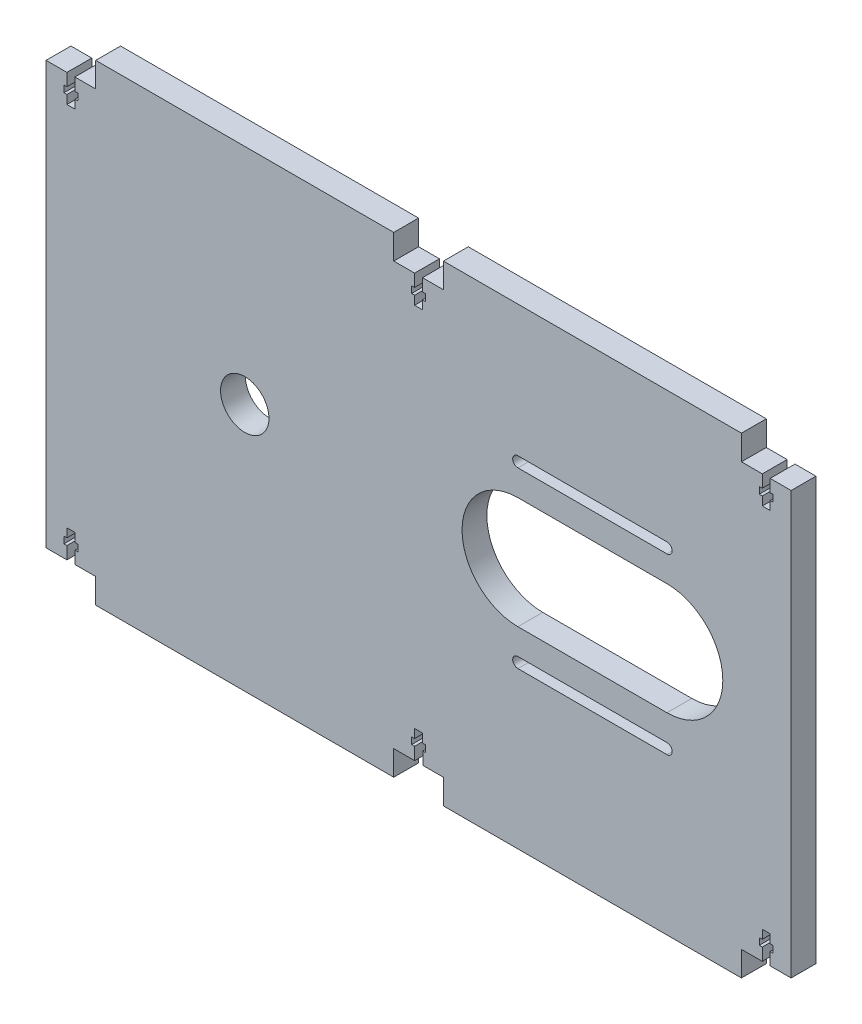
SolidWorks part; units mm, degrees
ref_plane "Ön Düzlem" through (0, 0, 0) normal (0, 0, 1) x (1, 0, 0)
ref_plane "Üst Düzlem" through (0, 0, 0) normal (0, 1, 0) x (1, 0, 0)
ref_plane "Sağ Düzlem" through (0, 0, 0) normal (1, 0, 0) x (0, 0, -1)
sketch "Çizim1" plane through (0, 0, 0) normal (0, 0, 1) x (1, 0, 0)
  line L0 (100, 10) -> (40, 10) construction
  line L1 (-150, -90) -> (150, -90)
  line L2 (-150, -90) -> (-150, 90)
  line L3 (-150, 90) -> (150, 90)
  line L4 (150, -90) -> (150, 90)
  line L5 (-150, -90) -> (150, 90) construction
  line L6 (-150, 90) -> (150, -90) construction
  line L7 (100, -12.5) -> (40, -12.5)
  line L8 (100, 32.5) -> (40, 32.5)
  line L9 (100, 45) -> (40, 45) construction
  line L10 (100, 42.9) -> (40, 42.9)
  line L11 (100, 47.1) -> (40, 47.1)
  line L12 (100, -25) -> (40, -25) construction
  line L13 (100, -27.1) -> (40, -27.1)
  line L14 (100, -22.9) -> (40, -22.9)
  arc A0 (100, -12.5) -> (100, 32.5) centre (100, 10) ccw
  circle A1 centre (-70, 10) radius 9.75
  arc A2 (40, 32.5) -> (40, -12.5) centre (40, 10) ccw
  arc A3 (100, 42.9) -> (100, 47.1) centre (100, 45) ccw
  arc A4 (40, 47.1) -> (40, 42.9) centre (40, 45) ccw
  arc A5 (100, -27.1) -> (100, -22.9) centre (100, -25) ccw
  arc A6 (40, -22.9) -> (40, -27.1) centre (40, -25) ccw
  point P0 (0, 0)
  point P8 (70, 10)
  point P17 (70, 45)
  point P22 (70, -25)
  dimension "D3" = 100
  dimension "D5" = 80
  dimension "D4" = 60
  dimension "D1" = 80
  dimension "D2" = 180
  dimension "D6" = 35
  dimension "D7" = 35
extrude "Yükseklik-Ekstrüzyon1" add sketch "Çizim1" along normal blind 10
sketch "Çizim2" plane through (0, 90, 0) normal (0, 1, 0) x (1, 0, 0)
  line L0 (130, -10) -> (130, 0)
  line L1 (130, -10) -> (10, -10)
  line L2 (130, 0) -> (10, 0)
  line L3 (10, -10) -> (10, 0)
  line L4 (150, -10) -> (-150, -10) construction
  line L5 (150, 0) -> (-150, 0) construction
  line L6 (150, -10) -> (150, 0) construction
  line L7 (-10, 0) -> (-10, -10)
  line L8 (-10, 0) -> (-130, 0)
  line L9 (-10, -10) -> (-130, -10)
  line L10 (-130, 0) -> (-130, -10)
  line L11 (-150, -10) -> (-150, 0) construction
  point P10 (0, 0)
  point P17 (0, 0)
  dimension "D1" = 20
  dimension "D2" = 10
  dimension "D3" = 20
  dimension "D4" = 10
extrude "Yükseklik-Ekstrüzyon2" add sketch "Çizim2" along normal blind 10
sketch "Çizim3" plane through (0, -90, 0) normal (0, -1, 0) x (-1, 0, 0)
  line L0 (150, -10) -> (150, 0)
  line L1 (150, -10) -> (130, -10)
  line L2 (150, 0) -> (130, 0)
  line L3 (130, -10) -> (130, 0)
  line L4 (-150, -10) -> (-150, 0)
  line L5 (-150, -10) -> (-130, -10)
  line L6 (-150, 0) -> (-130, 0)
  line L7 (-130, -10) -> (-130, 0)
  line L8 (10, 0) -> (10, -10)
  line L9 (10, 0) -> (-10, 0)
  line L10 (10, -10) -> (-10, -10)
  line L11 (-10, 0) -> (-10, -10)
  line L12 (150, 0) -> (-150, 0) construction
  line L13 (150, -10) -> (-150, -10) construction
  dimension "D1" = 120
  dimension "D2" = 20
  dimension "D3" = 20
  dimension "D4" = 20
extrude "Kes-Ekstrüzyon1" cut sketch "Çizim3" against normal blind 10
sketch "Çizim4" plane through (0, 0, 10) normal (0, 0, 1) x (1, 0, 0)
  line L0 (-142.8, 85) -> (-137.2, 85)
  line L1 (-142.8, 85) -> (-142.8, 82.3)
  line L2 (-137.2, 85) -> (-137.2, 82.3)
  line L3 (-142.8, 82.3) -> (-137.2, 82.3)
  line L4 (-130, 90) -> (-150, 90) construction
  line L5 (-10, 100) -> (-10, 90) construction
  line L6 (-2.8, 85) -> (2.8, 85)
  line L7 (-2.8, 85) -> (-2.8, 82.3)
  line L8 (-2.8, 82.3) -> (2.8, 82.3)
  line L9 (137.2, 85) -> (142.8, 85)
  line L10 (137.2, 85) -> (137.2, 82.3)
  line L11 (137.2, 82.3) -> (142.8, 82.3)
  line L12 (142.8, 85) -> (142.8, 82.3)
  line L13 (-130, -80) -> (-150, -80) construction
  line L14 (-142.8, -75) -> (-137.2, -75)
  line L15 (-142.8, -75) -> (-142.8, -72.3)
  line L16 (-142.8, -72.3) -> (-137.2, -72.3)
  line L17 (10, -80) -> (10, -90) construction
  line L18 (-2.8, -72.3) -> (2.8, -72.3)
  line L19 (-2.8, -72.3) -> (-2.8, -75)
  line L20 (-2.8, -75) -> (2.8, -75)
  line L21 (2.8, -72.3) -> (2.8, -75)
  line L22 (137.2, -72.3) -> (142.8, -72.3)
  line L23 (137.2, -72.3) -> (137.2, -75)
  line L24 (137.2, -75) -> (142.8, -75)
  line L25 (-150, 90) -> (-150, -80) construction
  line L27 (2.8, 85) -> (2.8, 82.3)
  line L28 (150, -80) -> (150, 90) construction
  line L29 (-137.2, -75) -> (-137.2, -72.3)
  line L30 (142.8, -72.3) -> (142.8, -75)
  dimension "D1" = 5
  dimension "D2" = 7.2
  dimension "D3" = 5.6
  dimension "D4" = 7.2
  dimension "D5" = 5.6
  dimension "D6" = 7.2
  dimension "D7" = 2.7
  dimension "D8" = 2.7
  dimension "D9" = 5
  dimension "D10" = 2.7
  dimension "D11" = 5.6
  dimension "D12" = 2.7
  dimension "D13" = 5.6
  dimension "D14" = 7.2
  dimension "D15" = 7.2
  dimension "D16" = 5.6
  dimension "D17" = 7.2
  dimension "D18" = 5.6
extrude "Kes-Ekstrüzyon2" cut sketch "Çizim4" against normal blind 10
sketch "Çizim5" plane through (0, 0, 10) normal (0, 0, 1) x (1, 0, 0)
  line L0 (-141.6, 82.3) -> (-138.4, 82.3)
  line L1 (-141.6, 82.3) -> (-141.6, 78.8)
  line L2 (-138.4, 82.3) -> (-138.4, 78.8)
  line L3 (-141.6, 78.8) -> (-138.4, 78.8)
  line L4 (-142.8, 82.3) -> (-137.2, 82.3) construction
  line L5 (-1.6, 82.3) -> (1.6, 82.3)
  line L6 (-1.6, 82.3) -> (-1.6, 78.8)
  line L7 (1.6, 82.3) -> (1.6, 78.8)
  line L8 (-1.6, 78.8) -> (1.6, 78.8)
  line L9 (-2.8, 82.3) -> (2.8, 82.3) construction
  line L10 (138.4, 82.3) -> (141.6, 82.3)
  line L11 (138.4, 82.3) -> (138.4, 78.8)
  line L12 (141.6, 82.3) -> (141.6, 78.8)
  line L13 (138.4, 78.8) -> (141.6, 78.8)
  line L14 (150, -80) -> (150, 90) construction
  line L15 (137.2, 82.3) -> (142.8, 82.3) construction
  line L16 (-141.6, -72.3) -> (-138.4, -72.3)
  line L17 (-141.6, -72.3) -> (-141.6, -68.8)
  line L18 (-138.4, -72.3) -> (-138.4, -68.8)
  line L19 (-141.6, -68.8) -> (-138.4, -68.8)
  line L20 (-137.2, -72.3) -> (-142.8, -72.3) construction
  line L21 (-1.6, -72.3) -> (1.6, -72.3)
  line L22 (-1.6, -72.3) -> (-1.6, -68.8)
  line L23 (1.6, -72.3) -> (1.6, -68.8)
  line L24 (-1.6, -68.8) -> (1.6, -68.8)
  line L25 (-1.6, 85) -> (-1.6, 90)
  line L26 (2.8, -72.3) -> (-2.8, -72.3) construction
  line L27 (138.4, -72.3) -> (141.6, -72.3)
  line L28 (138.4, -72.3) -> (138.4, -68.8)
  line L29 (141.6, -72.3) -> (141.6, -68.8)
  line L30 (138.4, -68.8) -> (141.6, -68.8)
  line L31 (-141.6, 85) -> (-138.4, 85)
  line L32 (142.8, -72.3) -> (137.2, -72.3) construction
  line L33 (-141.6, 85) -> (-141.6, 90.0914)
  line L34 (-138.4, 85) -> (-138.4, 90.0914)
  line L35 (-141.6, 90.0914) -> (-138.4, 90.0914)
  line L36 (-137.2, 85) -> (-142.8, 85) construction
  line L37 (-1.6, 85) -> (1.5689, 85)
  line L38 (-1.6, 90) -> (1.5689, 90)
  line L39 (1.5689, 85) -> (1.5689, 90)
  line L42 (2.8, 85) -> (-2.8, 85) construction
  line L43 (10, 90) -> (-10, 90) construction
  line L44 (138.4, 85) -> (138.4, 90)
  line L45 (138.4, 85) -> (141.5574, 85)
  line L46 (138.4, 90) -> (141.5574, 90)
  line L47 (141.5574, 85) -> (141.5574, 90)
  line L50 (142.8, 85) -> (137.2, 85) construction
  line L51 (150, 90) -> (130, 90) construction
  line L52 (138.4, -75) -> (138.4, -80)
  line L53 (138.4, -75) -> (141.5648, -75)
  line L54 (138.4, -80) -> (141.5648, -80)
  line L55 (141.5648, -75) -> (141.5648, -80)
  line L58 (137.2, -75) -> (142.8, -75) construction
  line L59 (150, -80) -> (130, -80) construction
  line L60 (-1.6, -75) -> (-1.6, -80)
  line L61 (-1.6, -75) -> (1.6832, -75)
  line L62 (-1.6, -80) -> (1.6832, -80)
  line L63 (1.6832, -75) -> (1.6832, -80)
  line L66 (-2.8, -75) -> (2.8, -75) construction
  line L67 (10, -80) -> (-10, -80) construction
  line L68 (-141.6, -75) -> (-141.6, -80)
  line L69 (-141.6, -75) -> (-138.3075, -75)
  line L70 (-141.6, -80) -> (-138.3075, -80)
  line L71 (-138.3075, -75) -> (-138.3075, -80)
  line L74 (-142.8, -75) -> (-137.2, -75) construction
  line L75 (-130, -80) -> (-150, -80) construction
  dimension "D1" = 3.2
  dimension "D2" = 1.2
  dimension "D3" = 3.5
  dimension "D4" = 3.5
  dimension "D5" = 3.2
  dimension "D6" = 1.2
  dimension "D7" = 1.2
  dimension "D8" = 3.2
  dimension "D9" = 3.5
  dimension "D10" = 3.5
  dimension "D11" = 3.2
  dimension "D12" = 1.2
  dimension "D13" = 3.5
  dimension "D14" = 1.2
  dimension "D15" = 3.5
  dimension "D16" = 8.4
  dimension "D17" = 3.2
extrude "Kes-Ekstrüzyon3" cut sketch "Çizim5" against normal blind 10
